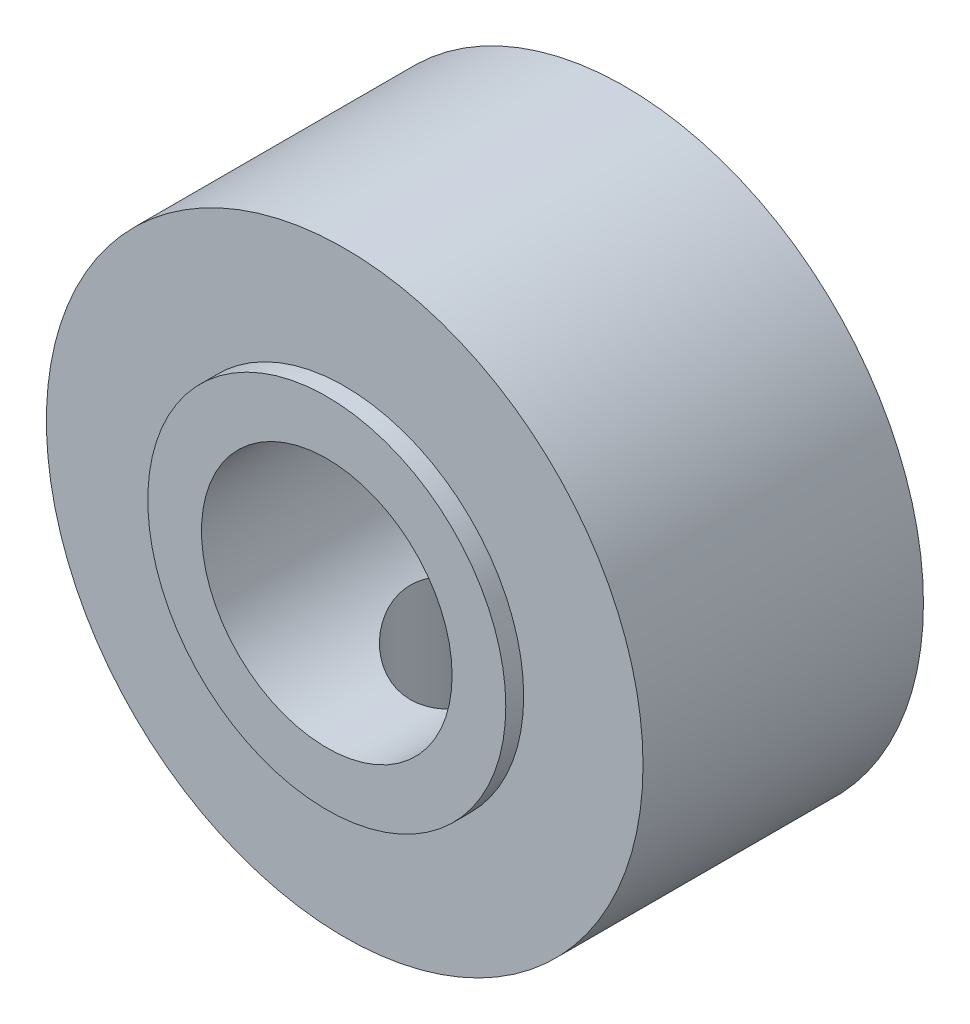
SolidWorks part; units mm, degrees
material "AISI 1020"
ref_plane "Face" through (0, 0, 0) normal (0, 0, 1) x (1, 0, 0)
ref_plane "Dessus" through (0, 0, 0) normal (0, 1, 0) x (1, 0, 0)
ref_plane "Droite" through (0, 0, 0) normal (1, 0, 0) x (0, 0, -1)
sketch "Esquisse1" plane through (0, 0, 0) normal (0, 0, 1) x (1, 0, 0)
  circle A0 centre (0, 0) radius 5
  dimension "D1" = 10
extrude "Boss.-Extru.1" add sketch "Esquisse1" along normal blind 4.7
sketch "Esquisse2" plane through (0, 0, 4.7) normal (0, 0, 1) x (1, 0, 0)
  circle A0 centre (0, 0) radius 3
  dimension "D1" = 6
extrude "Boss.-Extru.3" add sketch "Esquisse2" along normal offset from surface (0.3 mm away) 5 up to face at (5, 0, 0)
sketch "Esquisse3" plane through (0, 0, 5) normal (0, 0, 1) x (1, 0, 0)
  circle A0 centre (0, 0) radius 2.1
  dimension "D1" = 4.2
extrude "Enlèv. mat.-Extru.1" cut sketch "Esquisse3" against normal through all
sketch "Esquisse4" plane through (0, 0, 0) normal (0, 1, 0) x (1, 0, 0)
  line L0 (-5, -4.7) -> (5, -4.7) construction
  line L1 (5, 0) -> (-5, 0) construction
  line L2 (-5, -4.7) -> (5, -4.7) construction
  line L3 (5, 0) -> (-5, 0) construction
  line L4 (0, 0) -> (0, -4.7) construction
  circle A0 centre (0, -2.35) radius 1.25
  dimension "D1" = 2.5
extrude "Enlèv. mat.-Extru.2" cut sketch "Esquisse4" against normal through all
cosmetic thread "Représentation de filetage1" parameters "D2"=3
